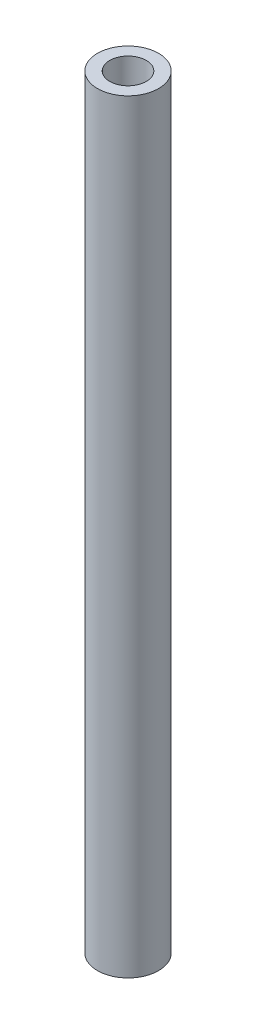
SolidWorks part; units mm, degrees
material "AISI 4130 Steel, annealed at 865C"
ref_plane "Front Plane" through (0, 0, 0) normal (0, 0, 1) x (1, 0, 0)
ref_plane "Top Plane" through (0, 0, 0) normal (0, 1, 0) x (1, 0, 0)
ref_plane "Right Plane" through (0, 0, 0) normal (1, 0, 0) x (0, 0, -1)
sketch "Sketch1" plane through (0, 0, 0) normal (0, 1, 0) x (1, 0, 0)
  circle A0 centre (0, 0) radius 3.175
  dimension "D1" = 6.35
extrude "Boss-Extrude1" add sketch "Sketch1" along normal blind 79.375
hole_wizard "Attachhment Hole" positions "Sketch3" profile "Sketch4" tap size "#10-24" standard "ANSI Inch"
sketch "Sketch3" plane through (0, 79.375, 0) normal (0, 1, 0) x (1, 0, 0)
  point P0 (0, 0)
sketch "Sketch4" plane through (0, 79.375, 0) normal (1, 0, 0) x (0, 0, 1)
  line L0 (0, 0) -> (0, 13.8408)
  line L1 (0, 13.8408) -> (1.8986, 12.7)
  line L2 (1.8986, 12.7) -> (1.8986, 0)
  line L5 (1.8986, 0) -> (0, 0)
  line L10 (0, 13.8408) -> (-1.8987, 12.7) construction
  line L11 (0, -6.35) -> (0, 107.95) construction
  dimension "Tap Drill Dia." = 3.7973
  dimension "Tap Drill Depth" = 12.7
  dimension "Drill Angle" = 118
cosmetic thread "Hole Thread1" parameters "D1"=9.652, "D2"=4.826
hole_wizard "#10-24 Tapped" positions "Sketch5" profile "Sketch6" tap size "#10-24" standard "ANSI Inch"
sketch "Sketch5" plane through (0, 0, 0) normal (0, -1, 0) x (-1, 0, 0)
  point P0 (0, 0)
sketch "Sketch6" plane through (0, 0, 0) normal (1, 0, 0) x (0, 0, -1)
  line L0 (0, 0) -> (0, 13.8408)
  line L1 (0, 13.8408) -> (1.8986, 12.7)
  line L2 (1.8986, 12.7) -> (1.8986, 0)
  line L5 (1.8986, 0) -> (0, 0)
  line L10 (0, 13.8408) -> (-1.8987, 12.7) construction
  line L11 (0, -6.35) -> (0, 107.95) construction
  dimension "Tap Drill Dia." = 3.7973
  dimension "Tap Drill Depth" = 12.7
  dimension "Drill Angle" = 118
cosmetic thread "Hole Thread2" parameters "D1"=9.652, "D2"=4.826
